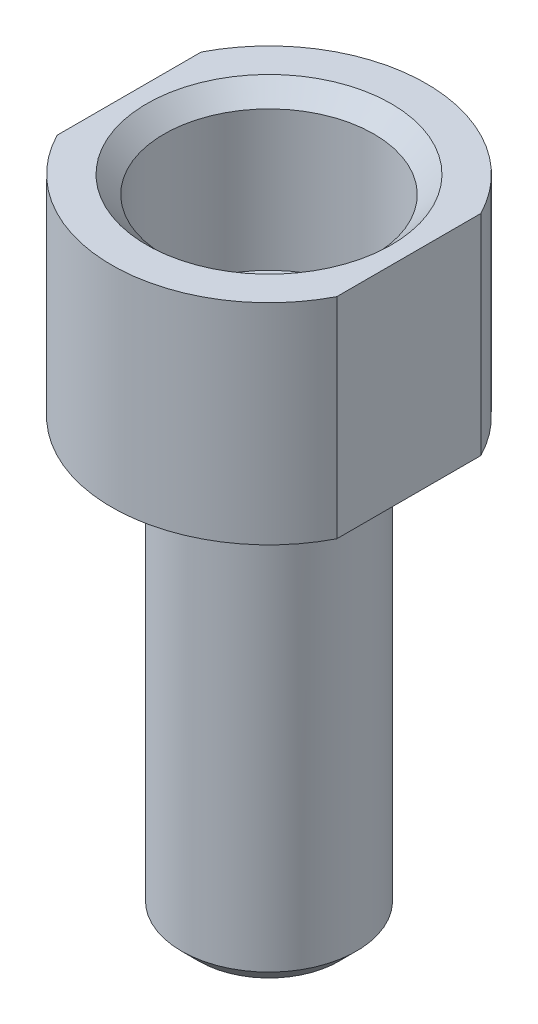
SolidWorks part; units mm, degrees
ref_plane "Plan de face" through (0, 0, 0) normal (0, 0, 1) x (1, 0, 0)
ref_plane "Plan de dessus" through (0, 0, 0) normal (0, 1, 0) x (1, 0, 0)
ref_plane "Plan de droite" through (0, 0, 0) normal (1, 0, 0) x (0, 0, -1)
sketch "Esquisse1" plane through (0, 0, 0) normal (0, 0, 1) x (1, 0, 0)
  line L0 (0, 0) -> (0, 29.7361) construction
  line L1 (3.3, 0) -> (3.3, 6)
  line L2 (2.5, 6) -> (2.5, 22)
  line L3 (2.5, 22) -> (3.3, 22)
  line L4 (3.3, 22) -> (3.3, 28)
  line L5 (3.3, 28) -> (6, 28)
  line L6 (6, 28) -> (6, 37)
  line L7 (6, 37) -> (9, 37)
  line L8 (9, 37) -> (9, 25)
  line L9 (9, 25) -> (7.56, 25)
  line L10 (7.56, 25) -> (7.56, 26.25)
  line L11 (7.56, 26.25) -> (5.41, 26.25)
  line L12 (5.41, 26.25) -> (5.41, 25)
  line L13 (5.41, 25) -> (5, 25)
  line L14 (5, 25) -> (5, 0)
  line L15 (5, 0) -> (3.3, 0)
  line L16 (3.3, 6) -> (2.5, 6)
  line L17 (3.3, 6) -> (2.5, 6)
  dimension "D1" = 25
  dimension "D2" = 12
  dimension "D3" = 7.56
  dimension "D4" = 9
  dimension "D5" = 5.41
  dimension "D6" = 5
  dimension "D7" = 3.3
  dimension "D8" = 6
  dimension "D9" = 9
  dimension "D10" = 15
  dimension "D11" = 31
  dimension "D12" = 2.5
  dimension "D13" = 1.25
revolve "Révolution1" add sketch "Esquisse1" angle 360 about L0
sketch "Esquisse2" plane through (0, 37, 0) normal (0, 1, 0) x (1, 0, 0)
  line L0 (0, 0) -> (0, 9) construction
  line L1 (-8, 4.1231) -> (-8, -4.1231)
  line L2 (8, 4.1231) -> (8, -4.1231)
  circle A0 centre (0, 0) radius 9 construction
  arc A1 (-8, 4.1231) -> (-8, -4.1231) centre (0, 0) ccw
  arc A2 (8, 4.1231) -> (8, -4.1231) centre (0, 0) cw
  dimension "D1" = 16
extrude "Enlèv. mat.-Extru.1" cut sketch "Esquisse2" against normal through all
chamfer "Chanfrein1" distance 1 angle 45 1 edges at (0, 37, -6)
chamfer "Chanfrein2" distance 0.5 angle 45 4 edges at (0, 6, -2.5) (0, 22, -2.5) (0, 28, -3.3) (0, 0, -3.3)
chamfer "Chanfrein3" distance 1 angle 45 1 edges at (0, 0, -5)
